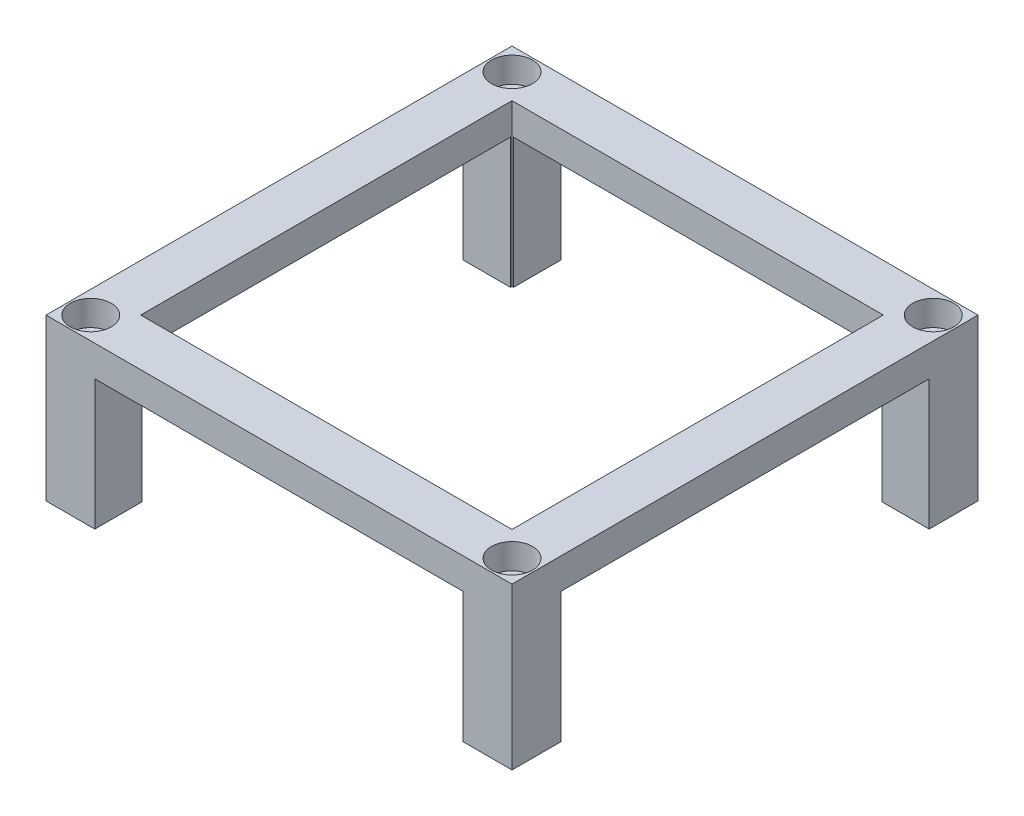
SolidWorks part; units mm, degrees
ref_plane "Front Plane" through (0, 0, 0) normal (0, 0, 1) x (1, 0, 0)
ref_plane "Top Plane" through (0, 0, 0) normal (0, 1, 0) x (1, 0, 0)
ref_plane "Right Plane" through (0, 0, 0) normal (1, 0, 0) x (0, 0, -1)
sketch "Sketch1" plane through (0, 0, 0) normal (0, 1, 0) x (1, 0, 0)
  line L1 (0, 0) -> (125, 0)
  line L2 (0, 0) -> (0, 125)
  line L3 (0, 125) -> (125, 125)
  line L4 (125, 0) -> (125, 125)
  dimension "D1" = 125
  dimension "D2" = 125
extrude "Extrude1" add sketch "Sketch1" along normal blind 43.18
sketch "Sketch2" plane through (0, 43.18, 0) normal (0, 1, 0) x (-1, 0, 0)
  line L0 (0, -125) -> (0, 0) construction
  line L1 (-12.7, -112.3) -> (-112.3, -112.3)
  line L2 (-12.7, -112.3) -> (-12.7, -12.7)
  line L3 (-12.7, -12.7) -> (-112.3, -12.7)
  line L4 (-112.3, -112.3) -> (-112.3, -12.7)
  line L5 (-125, -125) -> (0, -125) construction
  line L6 (-125, 0) -> (-125, -125) construction
  line L7 (0, 0) -> (-125, 0) construction
  dimension "D1" = 12.7
  dimension "D2" = 12.7
  dimension "D3" = 12.7
  dimension "D4" = 12.7
extrude "Cut-Extrude1" cut sketch "Sketch2" against normal through all
sketch "Sketch3" plane through (0, 0, 0) normal (0, 0, 1) x (1, 0, 0)
  line L0 (0, 0) -> (125, 0) construction
  line L2 (13.0926, 0) -> (111.9074, 0)
  line L3 (13.0926, 0) -> (13.0926, 34.925)
  line L5 (13.0926, 34.925) -> (111.9074, 34.925)
  line L6 (111.9074, 0) -> (111.9074, 34.925)
  line L7 (0, 43.18) -> (0, 0) construction
  line L8 (125, 43.18) -> (125, 0) construction
  dimension "D1" = 13.0926
  dimension "D2" = 13.0926
  dimension "D3" = 34.925
extrude "Cut-Extrude2" cut sketch "Sketch3" against normal through all
sketch "Sketch6" plane through (125, 0, 0) normal (1, 0, 0) x (0, 0, -1)
  line L0 (0, 0) -> (125, 0) construction
  line L2 (13.0926, 0) -> (111.9074, 0)
  line L3 (13.0926, 0) -> (13.0926, 34.925)
  line L5 (13.0926, 34.925) -> (111.9074, 34.925)
  line L6 (111.9074, 0) -> (111.9074, 34.925)
  line L7 (0, 43.18) -> (0, 0) construction
  line L8 (125, 43.18) -> (125, 0) construction
  dimension "D1" = 13.0926
  dimension "D2" = 13.0926
  dimension "D3" = 34.925
extrude "Cut-Extrude3" cut sketch "Sketch6" against normal through all
hole_wizard "打孔尺寸(%根据)内六角圆柱头螺钉的类型2" positions "Sketch8" profile "Sketch7" size "M6" standard "GB" slot yes end condition through all
sketch "Sketch8" plane through (0, 43.18, 0) normal (0, 1, 0) x (-1, 0, 0)
  line L0 (0, 0) -> (-125, 0) construction
  line L1 (0, -125) -> (0, 0) construction
  line L2 (-125, 0) -> (-125, -125) construction
  line L3 (-125, -125) -> (0, -125) construction
  point P0 (-6, -6)
  point P1 (-119, -6)
  point P2 (-119, -119)
  point P3 (-6, -119)
  dimension "D1" = 6
  dimension "D2" = 6
  dimension "D3" = 6
  dimension "D4" = 6
  dimension "D5" = 6
  dimension "D6" = 6
  dimension "D7" = 6
  dimension "D8" = 6
sketch "Sketch7" plane through (6, 43.18, -6) normal (1, 0, 0) x (0, 0, 1)
  line L0 (0, 0) -> (0, 43.18)
  line L1 (0, 43.18) -> (3.3, 43.18)
  line L3 (3.3, 43.18) -> (3.3, 6.8)
  line L4 (3.3, 6.8) -> (5.5, 6.8)
  line L5 (5.5, 6.8) -> (5.5, 0)
  line L7 (5.5, 0) -> (0, 0)
  line L11 (0, -6.35) -> (0, 107.95) construction
  dimension "Thru Hole Dia." = 6.6
  dimension "Thru Hole Depth" = 43.18
  dimension "C'Bore Dia." = 11
  dimension "C'Bore Depth" = 6.8
